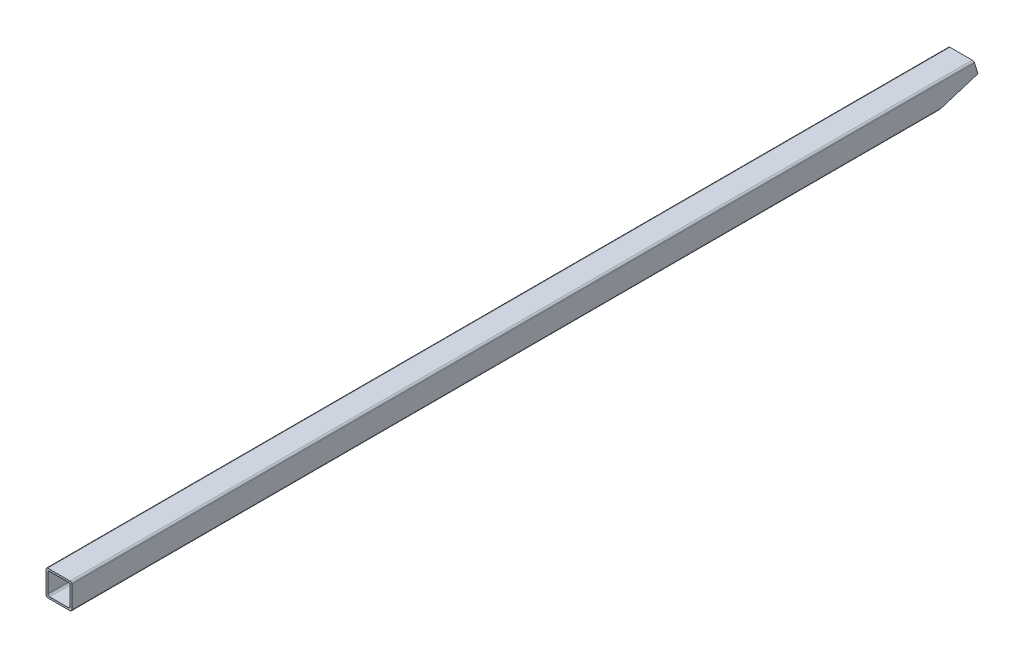
SolidWorks part; units mm, degrees
material "ASTM A500 Grade B"
ref_plane "Front Plane" through (0, 0, 0) normal (0, 0, 1) x (1, 0, 0)
ref_plane "Top Plane" through (0, 0, 0) normal (0, 1, 0) x (1, 0, 0)
ref_plane "Right Plane" through (0, 0, 0) normal (1, 0, 0) x (0, 0, -1)
sketch "Sketch1" plane through (0, 0, 0) normal (0, 0, 1) x (1, 0, 0)
  line L0 (5.3086, -2.7686) -> (32.7914, -2.7686)
  line L1 (2.54, 0) -> (35.56, 0)
  line L2 (0, -2.54) -> (0, -35.56)
  line L3 (2.54, -38.1) -> (35.56, -38.1)
  line L4 (38.1, -2.54) -> (38.1, -35.56)
  line L5 (35.3314, -5.3086) -> (35.3314, -32.7914)
  line L6 (5.3086, -35.3314) -> (32.7914, -35.3314)
  line L7 (2.7686, -5.3086) -> (2.7686, -32.7914)
  line L8 (0, 0) -> (0, -38.1) construction
  line L9 (0, -38.1) -> (38.1, -38.1) construction
  line L10 (38.1, 0) -> (38.1, -38.1) construction
  line L11 (2.7686, -2.7686) -> (2.7686, -35.3314) construction
  line L12 (2.7686, -35.3314) -> (35.3314, -35.3314) construction
  line L13 (35.3314, -2.7686) -> (35.3314, -35.3314) construction
  line L14 (2.7686, -2.7686) -> (35.3314, -2.7686) construction
  line L15 (0, 0) -> (38.1, 0) construction
  arc A0 (0, -35.56) -> (2.54, -38.1) centre (2.54, -35.56) ccw
  arc A1 (38.1, -35.56) -> (35.56, -38.1) centre (35.56, -35.56) cw
  arc A2 (2.7686, -32.7914) -> (5.3086, -35.3314) centre (5.3086, -32.7914) ccw
  arc A3 (32.7914, -35.3314) -> (35.3314, -32.7914) centre (32.7914, -32.7914) ccw
  arc A4 (35.3314, -5.3086) -> (32.7914, -2.7686) centre (32.7914, -5.3086) ccw
  arc A5 (38.1, -2.54) -> (35.56, 0) centre (35.56, -2.54) ccw
  arc A6 (0, -2.54) -> (2.54, 0) centre (2.54, -2.54) cw
  arc A7 (5.3086, -2.7686) -> (2.7686, -5.3086) centre (5.3086, -5.3086) ccw
  point P12 (0, -38.1)
  dimension "D4" = 2.54
  dimension "D3" = 2.7686
extrude "Boss-Extrude1" add sketch "Sketch1" along normal blind 1340
sketch "Sketch2" plane through (0, 0, 0) normal (-1, 0, 0) x (0, 0, 1)
  line L0 (0, -19.05) -> (5.9517, 0)
  line L1 (0, -2.54) -> (0, -35.56) construction
  line L2 (5.9517, 0) -> (0, 0)
  line L3 (0, -19.05) -> (60.975, -38.1)
  line L4 (1340, -38.1) -> (0, -38.1) construction
  line L5 (60.975, -38.1) -> (0, -38.1)
  line L6 (0, -38.1) -> (0, -19.05)
  line L7 (0, 0) -> (0, -38.1)
  line M4 (0, -2.54) -> (0, -35.56)
  line M5 (0, -35.56) -> (1340, -35.56)
  line M7 (1340, -2.54) -> (0, -2.54)
  dimension "D1" = 17.35
  dimension "D2" = 72.65
extrude "Cut-Extrude1" cut sketch "Sketch2" against normal through all contours L2 L7 L0 M7 | L0 M4 M7 | L3 M4 M5 | L6 L5 L3 M5
